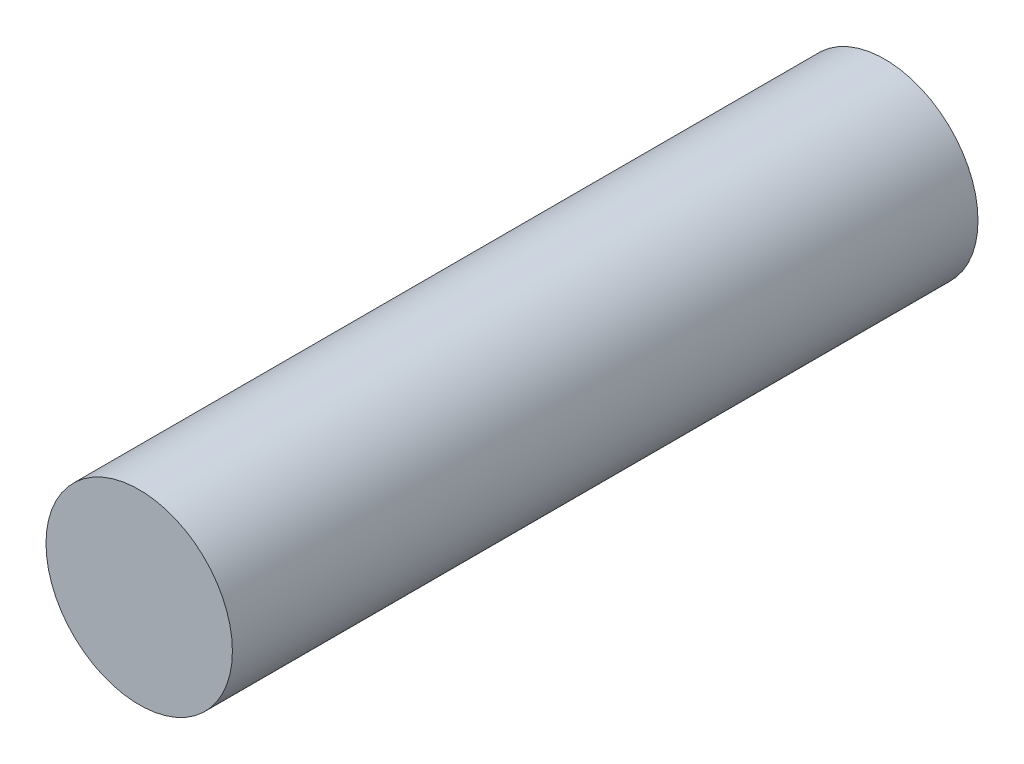
SolidWorks part; units mm, degrees
ref_plane "Front Plane" through (0, 0, 0) normal (0, 0, 1) x (1, 0, 0)
ref_plane "Top Plane" through (0, 0, 0) normal (0, 1, 0) x (1, 0, 0)
ref_plane "Right Plane" through (0, 0, 0) normal (1, 0, 0) x (0, 0, -1)
sketch "Sketch1" plane through (0, 0, 0) normal (0, 0, 1) x (1, 0, 0)
  circle A0 centre (0, 0) radius 4.7625
  dimension "D1" = 9.525
extrude "Boss-Extrude1" add sketch "Sketch1" along normal mid plane 38.1
sketch "Sketch2" plane through (0, 0, 0) normal (0, 1, 0) x (1, 0, 0)
  line L0 (-24.985, 0) -> (24.985, 0) construction
  line L1 (0, -23.9896) -> (0, 23.9896) construction
  line L2 (-22.4595, -6.35) -> (22.4595, -6.35) construction
  line L3 (-4.7625, -19.05) -> (4.7625, -19.05) construction
  line L4 (0, -6.35) -> (0, -33.8713) construction
  line L5 (0, -6.35) -> (-21.502, -33.8713)
  line L6 (0, -33.8713) -> (-29.0197, -33.8713) construction
  line L7 (9.8668, -36.219) -> (-31.3687, -4.0023) construction
  point P4 (0, 0)
  point P8 (0, 0)
  point P11 (0, -6.35)
  point P21 (-10.751, -20.1106)
  dimension "D1" = 12.7
  dimension "D2" = 38
